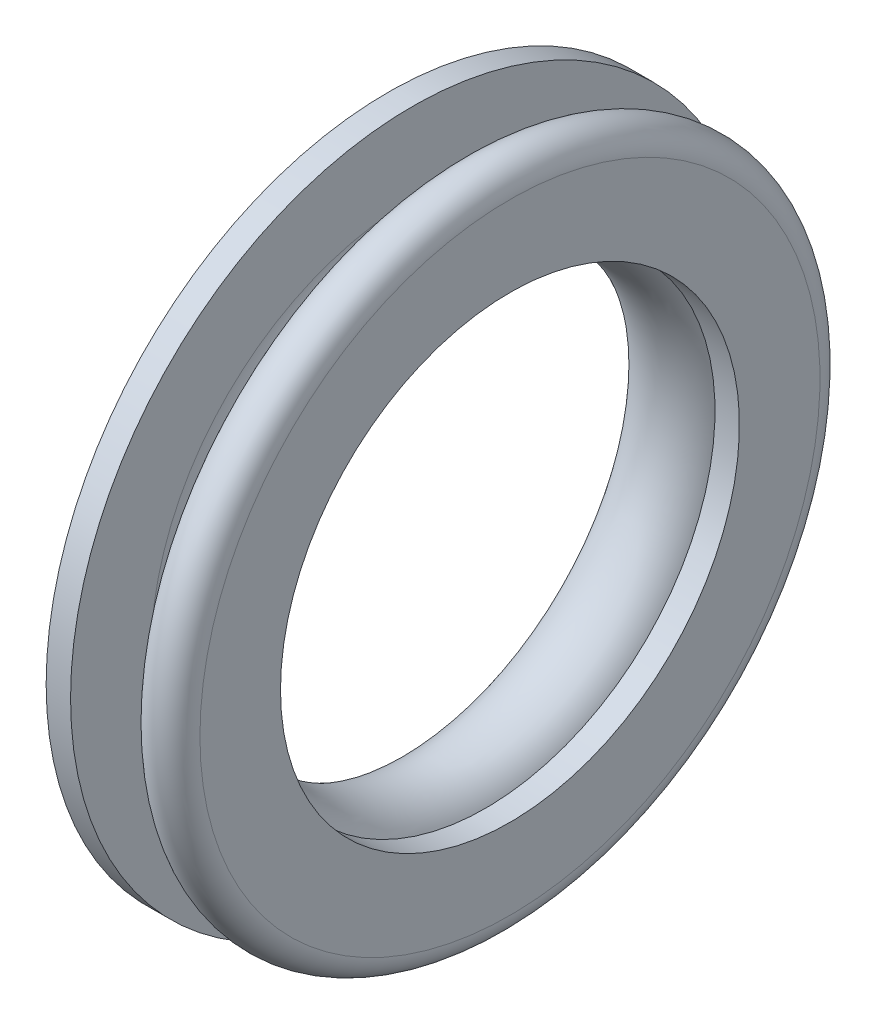
SolidWorks part; units mm, degrees
material "1.4028 (X30Cr13)"
ref_plane "Ön Düzlem" through (0, 0, 0) normal (0, 0, 1) x (1, 0, 0)
ref_plane "Üst Düzlem" through (0, 0, 0) normal (0, 1, 0) x (1, 0, 0)
ref_plane "Sağ Düzlem" through (0, 0, 0) normal (1, 0, 0) x (0, 0, -1)
sketch "Çizim1" plane through (0, 0, 0) normal (0, 0, 1) x (1, 0, 0)
  line L0 (0, 0) -> (0, 7) construction
  line L1 (0, 0) -> (12.0207, 0) construction
  line L2 (0, 7) -> (0, 5.35)
  line L3 (2, 5.35) -> (2, 6.35) construction
  line L4 (2, 4.7) -> (2.5, 4.7)
  line L5 (0.5, 7) -> (0.5, 5.35)
  line L6 (1.5, 5.35) -> (1.5, 6.35)
  line L7 (2.5, 6.35) -> (2.5, 4.7)
  line L8 (1.5, 6.35) -> (2.5, 6.35) construction
  line L9 (2, 6.35) -> (2, 4.7) construction
  line L10 (2, 4.7) -> (2, 5.35)
  line L11 (0, 7) -> (0.5, 7)
  arc A0 (0, 5.35) -> (2, 5.35) centre (1, 5.35) ccw
  arc A1 (1.5, 6.35) -> (2.5, 6.35) centre (2, 6.35) cw
  arc A2 (0.5, 5.35) -> (1.5, 5.35) centre (1, 5.35) ccw
  dimension "D2" = 1
  dimension "D4" = 0.5
  dimension "D1" = 7
  dimension "D3" = 1
  dimension "D5" = 1.65
  dimension "D6" = 1.65
  dimension "D7" = 0.5
  dimension "D9" = 0.5
revolve "Döndür1" add sketch "Çizim1" angle 360 about L1
